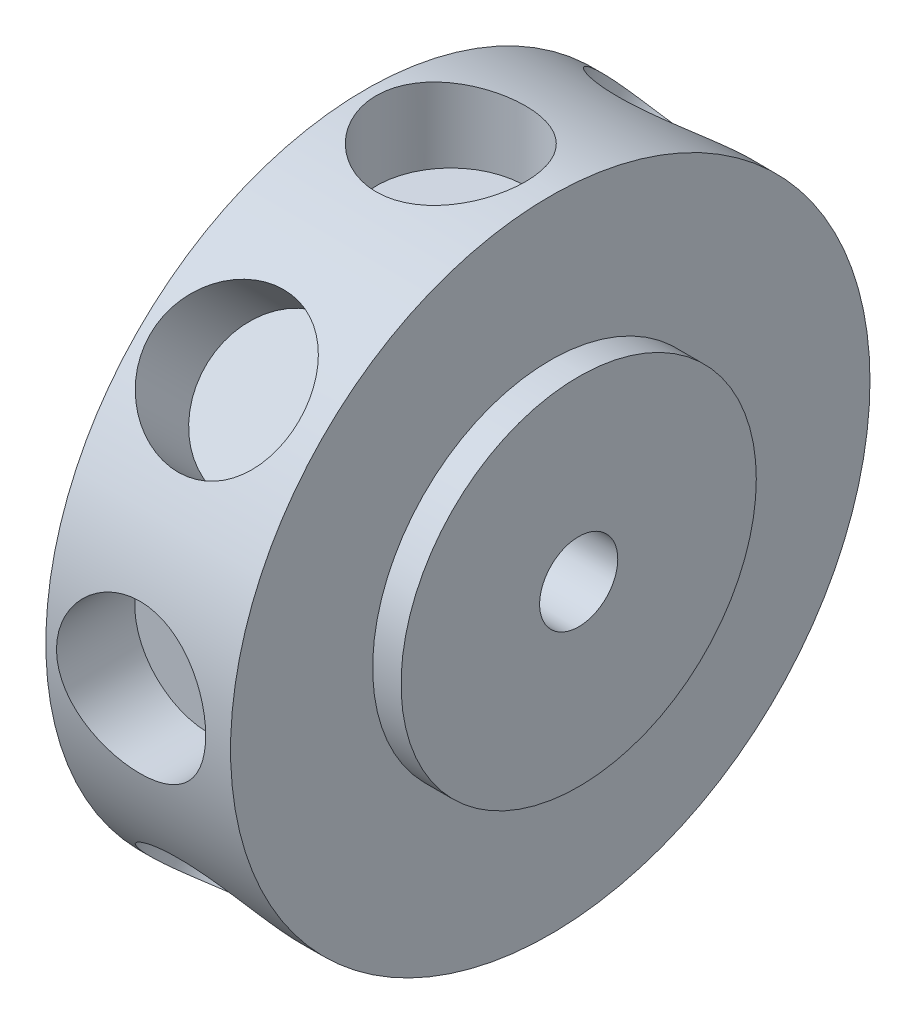
SolidWorks part; units mm, degrees
ref_plane "Front Plane" through (0, 0, 0) normal (0, 0, 1) x (1, 0, 0)
ref_plane "Top Plane" through (0, 0, 0) normal (0, 1, 0) x (1, 0, 0)
ref_plane "Right Plane" through (0, 0, 0) normal (1, 0, 0) x (0, 0, -1)
sketch "Sketch1" plane through (0, 0, 0) normal (1, 0, 0) x (0, 0, -1)
  circle A0 centre (0, 0) radius 22.5
  dimension "D1" = 45
extrude "Boss-Extrude1" add sketch "Sketch1" against normal blind 15
sketch "Sketch2" plane through (0, 0, 0) normal (1, 0, 0) x (0, 0, -1)
  circle A0 centre (0, 0) radius 2.75
  dimension "D1" = 5.5
extrude "Cut-Extrude1" cut sketch "Sketch2" against normal through all
sketch "Sketch5" plane through (-15, 0, 0) normal (-1, 0, 0) x (0, 0, 1)
  circle A0 centre (0, 0) radius 8.1
  dimension "D1" = 16.2
extrude "Cut-Extrude2" cut sketch "Sketch5" against normal blind 5.5
ref_plane "Plane1" through (0, 0, 22.5) normal (0, 0, 1) x (1, 0, 0)
sketch "Sketch6" plane through (0, 0, 22.5) normal (0, 0, 1) x (1, 0, 0)
  line L2 (-15, 22.5) -> (-15, -22.5) construction
  circle A0 centre (-9, 0) radius 5.25
  dimension "D1" = 10.5
  dimension "D2" = 6
extrude "Cut-Extrude3" cut sketch "Sketch6" against normal blind 5.5
pattern_circular "CirPattern1" count 8 over 360 about axis through (0, 0, 0) along (1, 0, 0) of "Cut-Extrude3"
ref_plane "Plane2" through (-1.5, 0, 0) normal (1, 0, 0) x (0, 0, -1)
sketch "Sketch29" plane through (0, 0, 0) normal (1, 0, 0) x (0, 0, -1)
  circle A0 centre (0, 0) radius 12.5
  point P2 (0, 0)
  dimension "D1" = 25
extrude "Cut-Extrude-Thin1" cut sketch "Sketch29" against normal blind 2 thin
